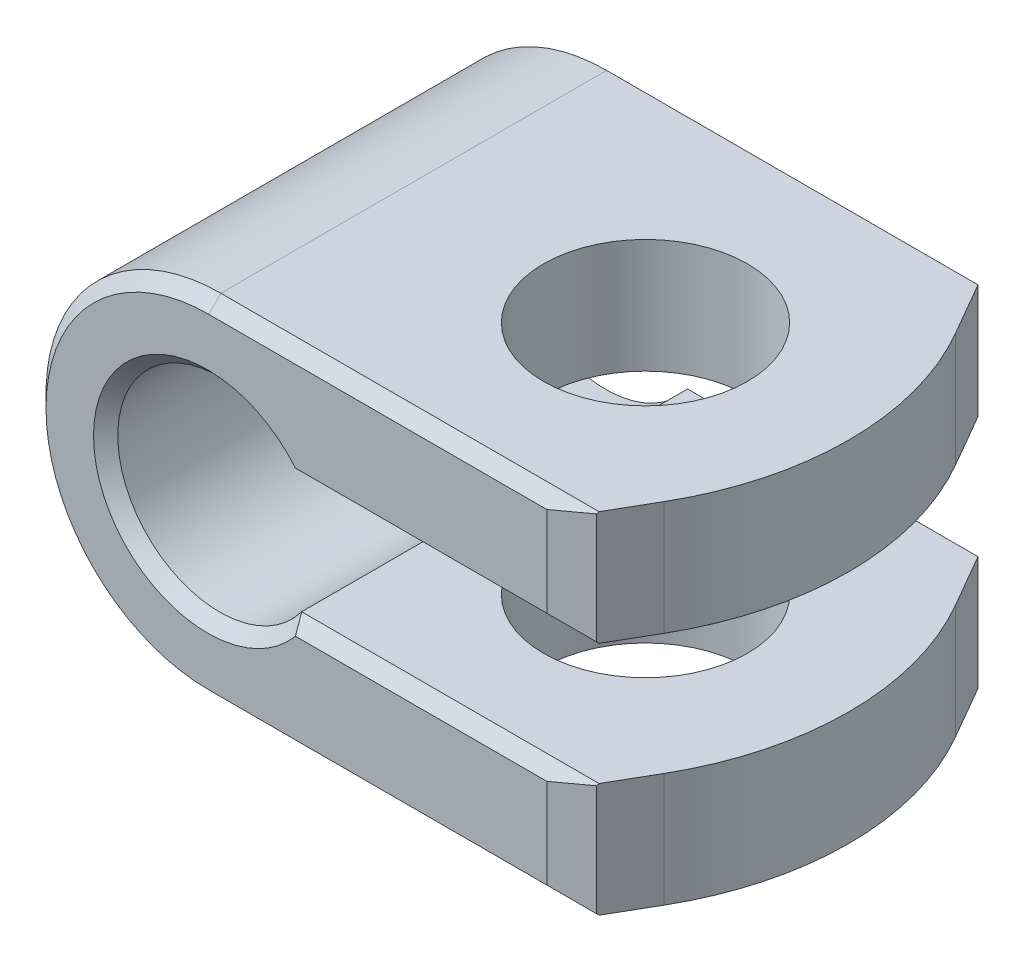
SolidWorks part; units mm, degrees
material "ABS"
ref_plane "Front Plane" through (0, 0, 0) normal (0, 0, 1) x (1, 0, 0)
ref_plane "Top Plane" through (0, 0, 0) normal (0, 1, 0) x (1, 0, 0)
ref_plane "Right Plane" through (0, 0, 0) normal (1, 0, 0) x (0, 0, -1)
ref_plane "Plane4" through (0, 0, 16.4) normal (0, 0, 1) x (1, 0, 0)
sketch "Sketch1" plane through (0, 0, 16.4) normal (0, 0, 1) x (1, 0, 0)
  line L0 (7.2, 0) -> (22.5, 0)
  line L1 (22.5, 0) -> (22.5, 14.4)
  line L2 (22.5, 14.4) -> (7.2, 14.4)
  arc A0 (7.2, 14.4) -> (7.2, 0) centre (7.2, 7.2) ccw
  dimension "D1" = 15.3
  dimension "D16" = 14.4
extrude "Boss-Extrude1" add sketch "Sketch1" against normal blind 16.4
sketch "Sketch2" plane through (0, 0, 0) normal (0, 0, -1) x (-1, 0, 0)
  line L0 (-22.5, 9.7) -> (-22.5, 4.7)
  line L1 (-22.5, 4.7) -> (-10.5327, 4.7)
  line L18 (-10.5327, 9.7) -> (-22.5, 9.7)
  arc A0 (-10.5327, 9.7) -> (-10.5327, 4.7) centre (-7.1578, 7.2) cw
  dimension "D1" = 4.2
extrude "Cut-Extrude1" cut sketch "Sketch2" against normal through all
sketch "Sketch4" plane through (0, 9.7, 0) normal (0, -1, 0) x (1, 0, 0)
  circle A1 centre (17, 8.2) radius 4.2
  dimension "D1" = 8.4
extrude "Cut-Extrude3" cut sketch "Sketch4" against normal through all both and the other way through all
sketch "Sketch5" plane through (0, 14.4, 0) normal (0, 1, 0) x (1, 0, 0)
  line L0 (22.5, 0) -> (22.5, -16.4)
  line L1 (22.5, -16.4) -> (27.2343, -8.2)
  line L2 (27.2343, -8.2) -> (22.5, 0)
  dimension "D1" = 30
extrude "Boss-Extrude2" add sketch "Sketch5" against normal up to surface (9.7 mm away)
ref_plane "Plane5" through (0, 7.2, 0) normal (0, -1, 0) x (-1, 0, 0)
mirror "Mirror3" about plane through (0, 7.2, 0) normal (0, -1, 0) of "Boss-Extrude2"
sketch "Sketch6" plane through (22.5, 0, 0) normal (-1, 0, 0) x (0, 0, 1)
  line L4 (0, 9.7) -> (0, 4.7)
  line L5 (0, 4.7) -> (16.4, 4.7)
  line L6 (16.4, 4.7) -> (16.4, 9.7)
  line L7 (16.4, 9.7) -> (0, 9.7)
  line L8 (0, 9.7) -> (0, 4.7)
  line L9 (0, 4.7) -> (16.4, 4.7)
  line L10 (16.4, 4.7) -> (16.4, 9.7)
  line L11 (16.4, 9.7) -> (0, 9.7)
  dimension "D1" = 0
extrude "Cut-Extrude4" cut sketch "Sketch6" against normal blind 10
fillet "Fillet1" radius 12 2 edges at (27.2343, 12.05, 8.2) (27.2343, 2.35, 8.2)
chamfer "Chamfer1" distance 0.5 angle 45 1 edges at (2.9578, 7.2, 16.4)
chamfer "Chamfer2" distance 0.5 angle 45 7 edges at (22.5, 12.05, 16.4) (22.5, 2.35, 16.4) (14.85, 0, 16.4) (0, 7.2, 16.4) (14.85, 14.4, 16.4) (16.8189, 9.7, 16.4) (16.8189, 4.7, 16.4)
